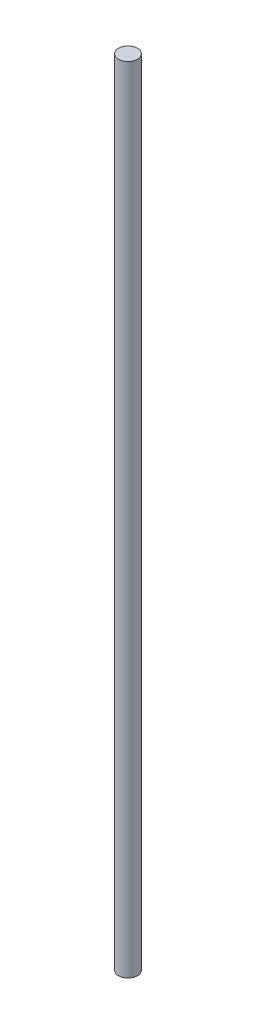
SolidWorks part; units mm, degrees
ref_plane "前视基准面" through (0, 0, 0) normal (0, 0, 1) x (1, 0, 0)
ref_plane "上视基准面" through (0, 0, 0) normal (0, 1, 0) x (1, 0, 0)
ref_plane "右视基准面" through (0, 0, 0) normal (1, 0, 0) x (0, 0, -1)
sketch "草图1" plane through (0, 0, 0) normal (0, 1, 0) x (1, 0, 0)
  circle A0 centre (0, 0) radius 3
extrude "凸台-拉伸1" add sketch "草图1" along normal blind 250
